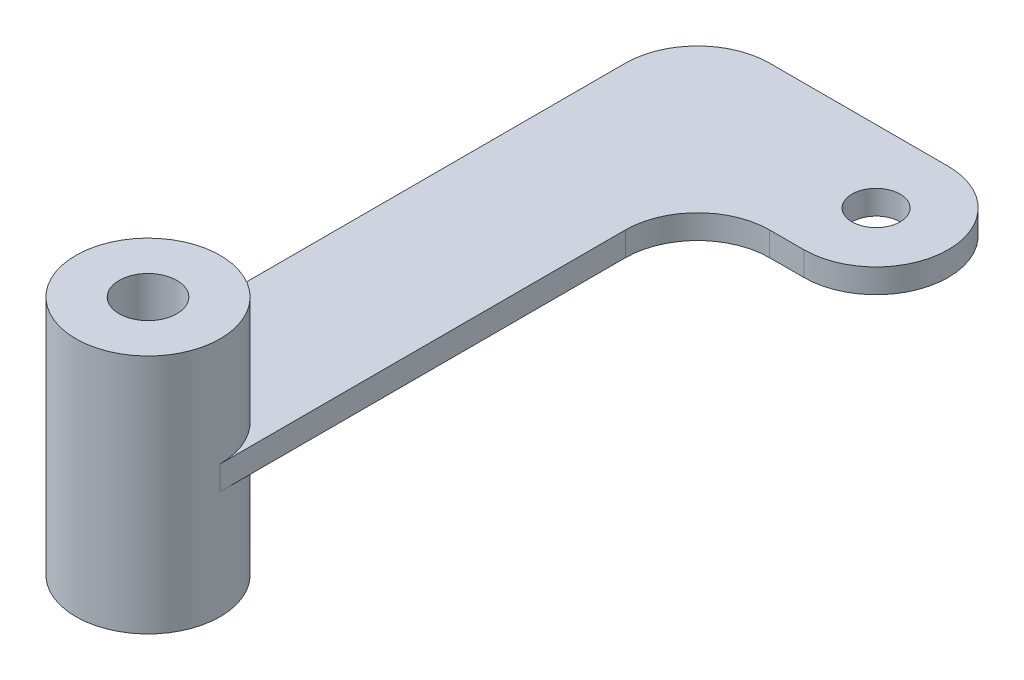
SolidWorks part; units mm, degrees
material "EN8"
ref_plane "Front Plane" through (0, 0, 0) normal (0, 0, 1) x (1, 0, 0)
ref_plane "Top Plane" through (0, 0, 0) normal (0, 1, 0) x (1, 0, 0)
ref_plane "Right Plane" through (0, 0, 0) normal (1, 0, 0) x (0, 0, -1)
sketch "Sketch4" plane through (0, 0, 0) normal (0, 0, 1) x (1, 0, 0)
  line L0 (0, 25) -> (0, -25) construction
  line L1 (0, 0) -> (5, 0) construction
  line L2 (5, 5) -> (5, -5)
  line L3 (5, 5) -> (6, 5)
  line L4 (6, 5) -> (6, 25)
  line L5 (6, 25) -> (15, 25)
  line L6 (15, 25) -> (15, -25)
  line L7 (15, -25) -> (6, -25)
  line L8 (6, -25) -> (6, -5)
  line L9 (6, -5) -> (5, -5)
  point P4 (0, 0)
  point P10 (5, 0)
  dimension "D1" = 50
  dimension "D2" = 5
  dimension "D3" = 10
  dimension "D4" = 15
  dimension "D5" = 1
  dimension "D6" = 20
revolve "Revolve1" add sketch "Sketch4" angle 360 about L0
sketch "Sketch5" plane through (0, 0, 0) normal (0, 0, 1) x (1, 0, 0)
  line L0 (0, 25) -> (0, -25) construction
  line L1 (-15, -25) -> (15, -25) construction
  line L2 (-4.3412, 24.6202) -> (4.3412, -24.6202) construction
  line L3 (0, 0) -> (-15.7569, -2.7784) construction
  point P6 (0, 0)
  point P10 (0, 0)
  point P11 (0, 0)
  dimension "D1" = 10
  dimension "D2" = 16
sketch "Sketch6" plane through (0, 0, 0) normal (0, 0, 1) x (1, 0, 0)
  line L0 (0, -30) -> (0, 30) construction
  point P4 (0, 0)
  dimension "D1" = 60
sketch "Sketch7" plane through (0, 0, 0) normal (0, 1, 0) x (1, 0, 0)
  line L0 (0, 0) -> (37.082, 114.1268) construction
  line L1 (-15, 0) -> (-15, 12.5)
  line L2 (-4.3412, 0) -> (4.3412, 0) construction
  line L3 (0, 0) -> (0, 114.1268) construction
  line L4 (0, 0) -> (-15.7569, 0) construction
  line L5 (15, 0) -> (15, 99.1268)
  line L8 (15, 99.1268) -> (37.082, 99.1268)
  line L9 (0, 114.1268) -> (37.082, 114.1268) construction
  line L10 (-15, 129.1268) -> (-15, 12.5)
  line L11 (-15, 129.1268) -> (37.082, 129.1268)
  line L12 (-15, 0) -> (-15, 129.1268) construction
  line L13 (-15, 12.5) -> (-8.2916, 12.5)
  circle A0 centre (37.082, 114.1268) radius 5
  arc A1 (32.4468, 99.8609) -> (37.082, 129.1268) centre (37.082, 114.1268) ccw
  circle A2 centre (0, 0) radius 15 construction
  circle A3 centre (0, 0) radius 15
  circle A4 centre (0, 0) radius 15
  arc A5 (15, 0) -> (0, 15) centre (0, 0) ccw
  dimension "D3" = 0
  dimension "D4" = 10
  dimension "D1" = 72
  dimension "D2" = 120
  dimension "D6" = 15
  dimension "D7" = 12.5
extrude "Boss-Extrude1" add sketch "Sketch7" along normal mid plane 5
fillet "Fillet3" radius 15 2 edges at (15, 0, -99.1268) (-15, 0, -129.1268)
